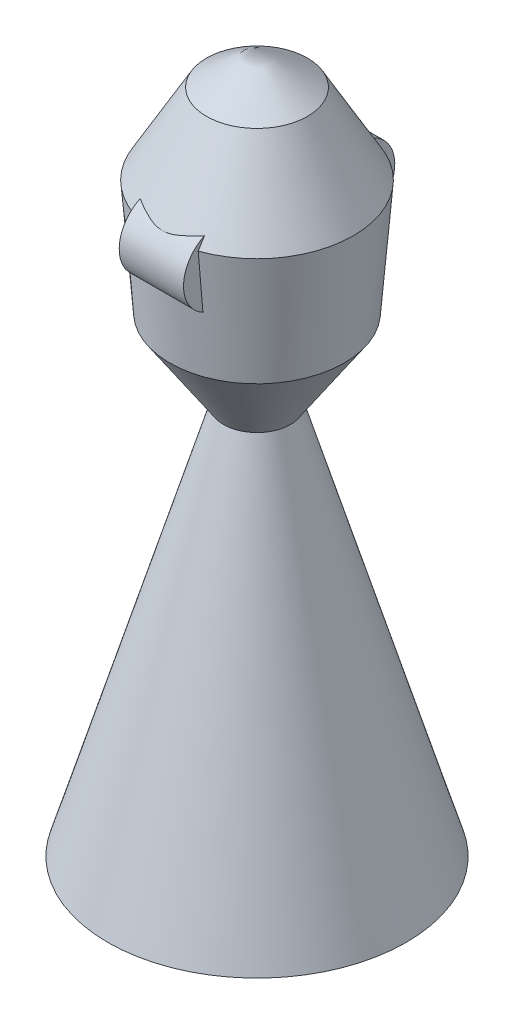
SolidWorks part; units mm, degrees
ref_plane "Front Plane" through (0, 0, 0) normal (0, 0, 1) x (1, 0, 0)
ref_plane "Top Plane" through (0, 0, 0) normal (0, 1, 0) x (1, 0, 0)
ref_plane "Right Plane" through (0, 0, 0) normal (1, 0, 0) x (0, 0, -1)
sketch "Sketch1" plane through (0, 0, 0) normal (0, 0, 1) x (1, 0, 0)
  line L0 (0, 0) -> (0, 3100) construction
  line L1 (0, 3100) -> (220, 2950)
  line L2 (220, 2950) -> (420, 2600)
  line L3 (420, 2600) -> (380, 2100)
  line L4 (380, 2100) -> (145, 1750)
  line L5 (145, 1750) -> (650, 50)
  line L6 (650, 50) -> (620, 50)
  line L7 (620, 50) -> (125, 1750)
  line L8 (125, 1750) -> (340, 2100)
  line L9 (340, 2100) -> (340, 2600)
  line L10 (340, 2600) -> (0, 2600)
  line L11 (0, 2600) -> (0, 3100)
revolve "Revolve1" add sketch "Sketch1" angle 360 about L0
sketch "Sketch2" plane through (0, 0, 0) normal (1, 0, 0) x (0, 0, -1)
  circle A0 centre (300, 2500) radius 160
  circle A1 centre (-300, 2500) radius 160
extrude "Boss-Extrude1" add sketch "Sketch2" along normal mid plane 280
